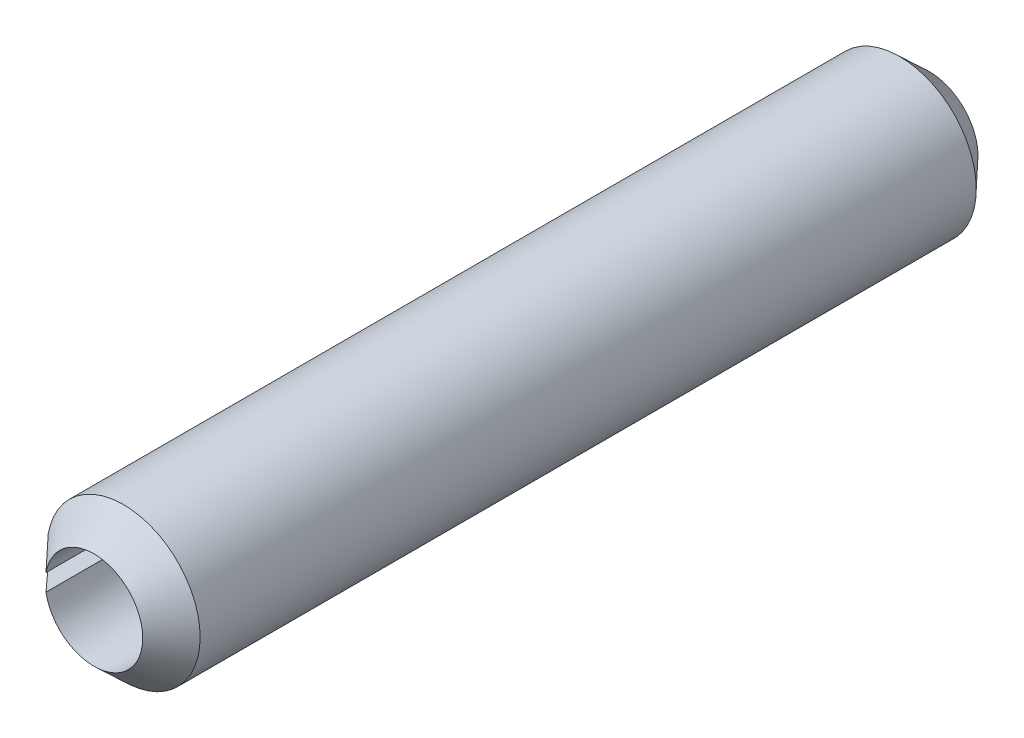
SolidWorks part; units mm, degrees
ref_plane "Front Plane" through (0, 0, 0) normal (0, 0, 1) x (1, 0, 0)
ref_plane "Top Plane" through (0, 0, 0) normal (0, 1, 0) x (1, 0, 0)
ref_plane "Right Plane" through (0, 0, 0) normal (1, 0, 0) x (0, 0, -1)
sketch "Sketch1" plane through (0, 0, 0) normal (0, 0, 1) x (1, 0, 0)
  line L0 (1.4, 0) -> (2.2, 0) construction
  line L1 (-2.1666, 0.382) -> (-1.3787, 0.2431)
  line L2 (-1.3787, -0.2431) -> (-2.1666, -0.382)
  arc A0 (-2.1666, -0.382) -> (-2.1666, 0.382) centre (0, 0) ccw
  arc A1 (-1.3787, -0.2431) -> (-1.3787, 0.2431) centre (0, 0) ccw
  dimension "OD" = 4.4
  dimension "Wall thickness" = 0.8
  dimension "D3" = 20
extrude "Extrude1" add sketch "Sketch1" along normal mid plane 24
sketch "Sketch2" plane through (0, 0, 0) normal (1, 0, 0) x (0, 0, -1)
  line L0 (0, -2.2) -> (0, 2.2) construction
  line L1 (12, 0) -> (-12, 0) construction
  line L2 (12, -1.4) -> (12, 1.4) construction
  line L3 (12, 2.2) -> (-12, 2.2) construction
  line L4 (12, 2.2) -> (12, 1.4)
  line L5 (12, 1.4) -> (11.15, 2.2)
  line L6 (11.15, 2.2) -> (12, 2.2)
  line L7 (12, -2.2) -> (12, 2.2) construction
  line L8 (-11.15, 2.2) -> (-12, 2.2)
  line L9 (-12, 1.4) -> (-11.15, 2.2)
  line L10 (-12, 2.2) -> (-12, 1.4)
  line L11 (11.15, -2.2) -> (12, -2.2) construction
  line L12 (12, -1.4) -> (11.15, -2.2) construction
  line L13 (12, -2.2) -> (12, -1.4) construction
  dimension "B" = 2.8
  dimension "Chamfer max" = 0.85
revolve "Cut-Revolve1" cut sketch "Sketch2" angle 360 about L1
sketch "Sketch3" plane through (0, 0, 0) normal (0, 0, 1) x (1, 0, 0)
  line L0 (1.4, 0) -> (2.2, 0) construction
  line L1 (1.4, 0) -> (2.2, 0)
  circle A0 centre (0, 0) radius 2.2
  circle A1 centre (0, 0) radius 1.4
  arc A2 (-2.1666, -0.382) -> (-2.1666, 0.382) centre (0, 0) ccw construction
  arc A3 (-1.3787, -0.2431) -> (-1.3787, 0.2431) centre (0, 0) ccw construction
